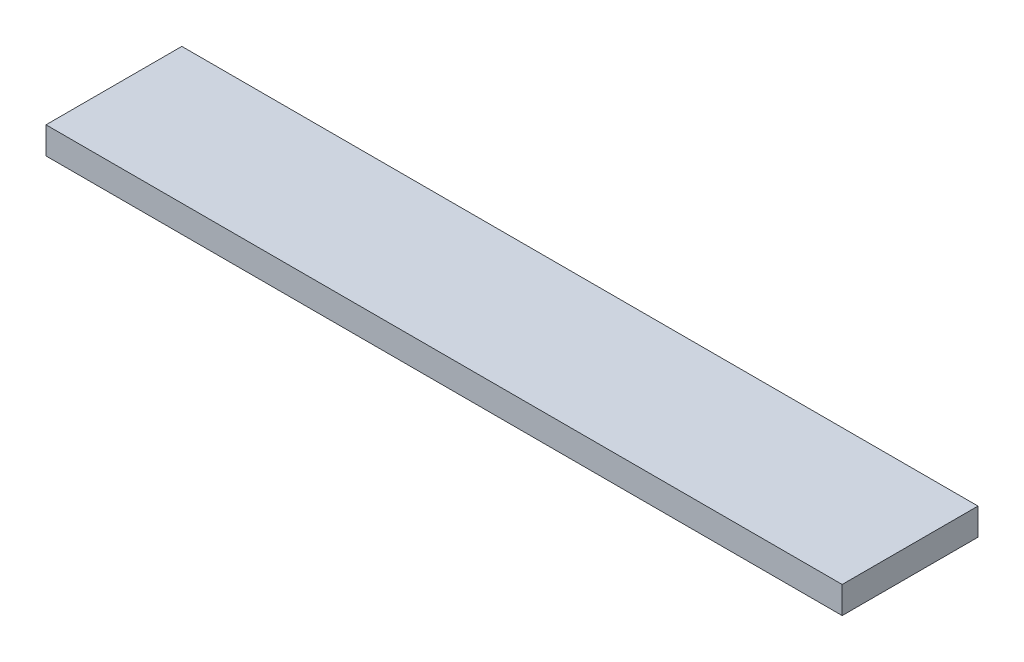
SolidWorks part; units mm, degrees
ref_plane "Front Plane" through (0, 0, 0) normal (0, 0, 1) x (1, 0, 0)
ref_plane "Top Plane" through (0, 0, 0) normal (0, 1, 0) x (1, 0, 0)
ref_plane "Right Plane" through (0, 0, 0) normal (1, 0, 0) x (0, 0, -1)
sketch "Sketch1" plane through (0, 0, 0) normal (0, 1, 0) x (1, 0, 0)
  line L1 (0, 0) -> (236, 0)
  line L2 (0, 0) -> (0, 40.26)
  line L3 (0, 40.26) -> (236, 40.26)
  line L4 (236, 0) -> (236, 40.26)
  dimension "D1" = 236
  dimension "D2" = 40.26
extrude "Boss-Extrude1" add sketch "Sketch1" along normal blind 8
